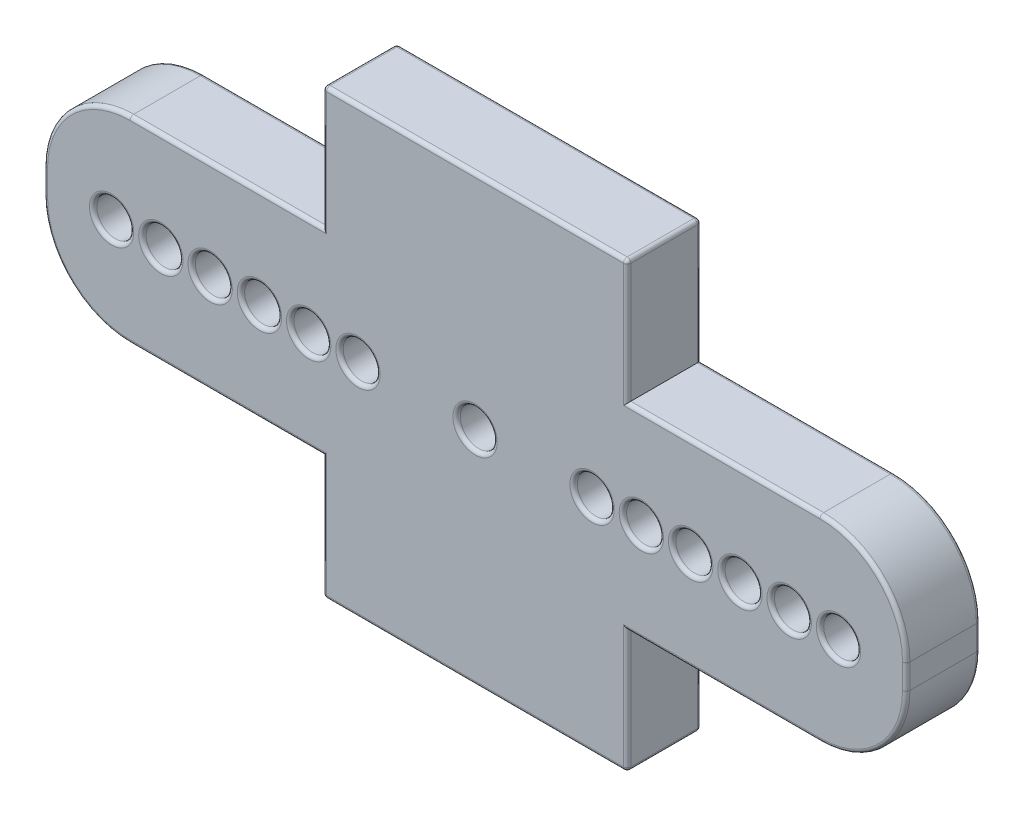
SolidWorks part; units mm, degrees
ref_plane "Front Plane" through (0, 0, 0) normal (0, 0, 1) x (1, 0, 0)
ref_plane "Top Plane" through (0, 0, 0) normal (0, 1, 0) x (1, 0, 0)
ref_plane "Right Plane" through (0, 0, 0) normal (1, 0, 0) x (0, 0, -1)
sketch "Sketch1" plane through (0, 0, 0) normal (0, 0, 1) x (1, 0, 0)
  line L0 (-17.5, 0.5) -> (-17.5, -0.5)
  line L1 (-6.175, -9) -> (6.175, -9) construction
  line L2 (-6.175, -9) -> (-6.175, 9) construction
  line L3 (-6.175, 9) -> (6.175, 9) construction
  line L4 (6.175, -9) -> (6.175, 9) construction
  line L5 (-6.175, -9) -> (6.175, 9) construction
  line L6 (-6.175, 9) -> (6.175, -9) construction
  line L7 (-17.5, -4) -> (17.5, -4) construction
  line L8 (-17.5, -4) -> (-17.5, 4) construction
  line L9 (-17.5, 4) -> (17.5, 4) construction
  line L10 (17.5, -4) -> (17.5, 4) construction
  line L11 (-17.5, -4) -> (17.5, 4) construction
  line L12 (-17.5, 4) -> (17.5, -4) construction
  line L13 (-14, -4) -> (-6.175, -4)
  line L14 (-6.175, -4) -> (-6.175, -9)
  line L15 (-6.175, -9) -> (6.175, -9)
  line L16 (6.175, -9) -> (6.175, -4)
  line L17 (6.175, -4) -> (14, -4)
  line L18 (17.5, -0.5) -> (17.5, 0.5)
  line L19 (14, 4) -> (6.175, 4)
  line L20 (6.175, 4) -> (6.175, 9)
  line L21 (6.175, 9) -> (-6.175, 9)
  line L22 (-6.175, 9) -> (-6.175, 4)
  line L23 (-6.175, 4) -> (-14, 4)
  circle A0 centre (0, 0) radius 0.75
  arc A1 (17.5, 0.5) -> (14, 4) centre (14, 0.5) ccw
  arc A2 (14, -4) -> (17.5, -0.5) centre (14, -0.5) ccw
  arc A3 (-17.5, -0.5) -> (-14, -4) centre (-14, -0.5) ccw
  arc A4 (-17.5, 0.5) -> (-14, 4) centre (-14, 0.5) cw
  point P0 (0, 0)
  point P6 (0, 0)
  dimension "D5" = 1.5
  dimension "D6" = 3.5
  dimension "D1" = 8
  dimension "D2" = 35
  dimension "D3" = 18
  dimension "D4" = 12.35
extrude "Boss-Extrude1" add sketch "Sketch1" along normal mid plane 3
sketch "Sketch2" plane through (0, 0, 1.5) normal (0, 0, 1) x (1, 0, 0)
  line L0 (-17.5, 0.5) -> (-17.5, -0.5) construction
  line L1 (0, 0) -> (-22.1541, 0) construction
  circle A0 centre (-14.75, 0) radius 0.75
  circle A1 centre (-12.75, 0) radius 0.75
  circle A2 centre (-10.75, 0) radius 0.75
  circle A3 centre (-8.75, 0) radius 0.75
  circle A4 centre (-6.75, 0) radius 0.75
  circle A5 centre (-4.75, 0) radius 0.75
  point P9 (-4.75, 0)
  dimension "D1" = 1.5
  dimension "D2" = 2.75
  dimension "D3" = 6
extrude "Cut-Extrude1" cut sketch "Sketch2" against normal through all
mirror "Mirror1" about plane through (0, 0, 0) normal (1, 0, 0) of "Cut-Extrude1"
fillet "Fillet1" radius 0.15 62 edges at (4, 0, 1.5) (4, 0, -1.5) (6, 0, 1.5) (6, 0, -1.5) (8, 0, 1.5) (8, 0, -1.5) (10, 0, 1.5) (10, 0, -1.5) (12, 0, 1.5) (12, 0, -1.5) (14, 0, 1.5) (14, 0, -1.5) (-4, 0, -1.5) (-4, 0, 1.5) (-6, 0, -1.5) (-6, 0, 1.5) (-8, 0, -1.5) (-8, 0, 1.5) (-10, 0, -1.5) (-10, 0, 1.5) (-12, 0, -1.5) (-12, 0, 1.5) (-14, 0, 1.5) (-14, 0, -1.5) (0.75, 0, -1.5) (0.75, 0, 1.5) (0, 9, -1.5) (-6.175, 6.5, -1.5) (-10.0875, 4, -1.5) (-17.5, 0, -1.5) (-10.0875, -4, -1.5) (-6.175, -6.5, -1.5) (0, -9, -1.5) (6.175, -6.5, -1.5) (10.0875, -4, -1.5) (17.5, 0, -1.5) (10.0875, 4, -1.5) (6.175, 6.5, -1.5) (0, 9, 1.5) (-6.175, 6.5, 1.5) (-10.0875, 4, 1.5) (-17.5, 0, 1.5) (-10.0875, -4, 1.5) (-6.175, -6.5, 1.5) (0, -9, 1.5) (6.175, -6.5, 1.5) (10.0875, -4, 1.5) (17.5, 0, 1.5) (10.0875, 4, 1.5) (6.175, 6.5, 1.5) (6.175, 9, 0) (6.175, -9, 0) (-6.175, -9, 0) (-6.175, 9, 0) (-16.4749, 2.9749, -1.5) (-16.4749, -2.9749, -1.5) (16.4749, -2.9749, -1.5) (16.4749, 2.9749, -1.5) (-16.4749, 2.9749, 1.5) (-16.4749, -2.9749, 1.5) (16.4749, -2.9749, 1.5) (16.4749, 2.9749, 1.5)
